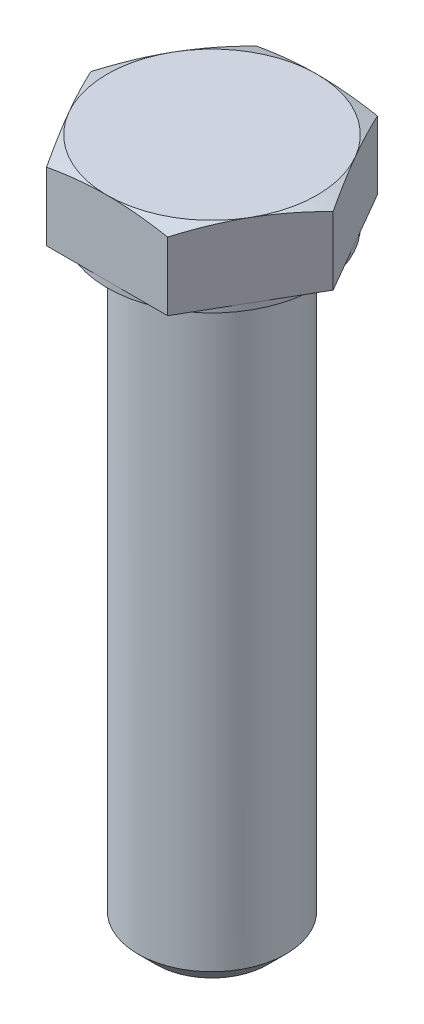
SolidWorks part; units mm, degrees
ref_plane "Front Plane" through (0, 0, 0) normal (0, 0, 1) x (1, 0, 0)
ref_plane "Top Plane" through (0, 0, 0) normal (0, 1, 0) x (1, 0, 0)
ref_plane "Right Plane" through (0, 0, 0) normal (1, 0, 0) x (0, 0, -1)
sketch "Sketch1" plane through (0, 0, 0) normal (0, 1, 0) x (1, 0, 0)
  circle A0 centre (0, 0) radius 12
extrude "Boss-Extrude1" add sketch "Sketch1" along normal blind 100
sketch "Sketch2" plane through (0, 100, 0) normal (0, 1, 0) x (1, 0, 0)
  line L1 (19.6299, 0) -> (9.815, 17)
  line L2 (9.815, 17) -> (-9.815, 17)
  line L3 (-9.815, 17) -> (-19.6299, 0)
  line L4 (-19.6299, 0) -> (-9.815, -17)
  line L5 (-9.815, -17) -> (9.815, -17)
  line L6 (9.815, -17) -> (19.6299, 0)
  circle A0 centre (0, 0) radius 17 construction
  dimension "D1" = 34
extrude "Boss-Extrude2" add sketch "Sketch2" along normal blind 12 contours L6 L1 L2 L3 L4 L5
sketch "Sketch4" plane through (0, 112, 0) normal (0, 1, 0) x (1, 0, 0)
  circle A0 centre (0, 0) radius 17
extrude "Cut-Extrude1" cut sketch "Sketch4" against normal blind 12 draft 70 flip side to cut
sketch "Sketch5" plane through (0, 100, 0) normal (0, -1, 0) x (1, 0, 0)
  line L0 (19.6299, 0) -> (9.815, -17) construction
  circle A0 centre (0, 0) radius 17
  circle A1 centre (17, -4.5551) radius 0.7134
  circle M2 centre (0, 0) radius 12
extrude "Boss-Extrude3" add sketch "Sketch5" along normal blind 1 contours A1 A0 M2
chamfer "Chamfer1" distance 3 angle 45 1 edges at (0, 0, 12)
sketch "Sketch7" plane through (0, 0, 0) normal (0, -1, 0) x (1, 0, 0)
  circle A0 centre (0, 0) radius 12 construction
  circle A1 centre (0, 0) radius 12
curve "Helix/Spiral1" pitch 3 height 80 turns 26.6667
sketch "Sketch8" plane through (0, 0, 0) normal (1, 0, 0) x (0, 0, -1)
  line L1 (83.329, -205.697) -> (79.7436, -211.907)
  line L2 (79.7436, -211.907) -> (86.9143, -211.907)
  line L3 (86.9143, -211.907) -> (83.329, -205.697)
  circle A0 centre (83.329, -209.837) radius 2.07 construction
  point P1 (0, 0)
  point P6 (83.329, -211.907)
  point P7 (0, 0)
  point P8 (0, 0)
  point P9 (0, 0)
  point P10 (0, 0)
  point P11 (0, 0)
  point P12 (0, 0)
  dimension "D1" = 2.07
